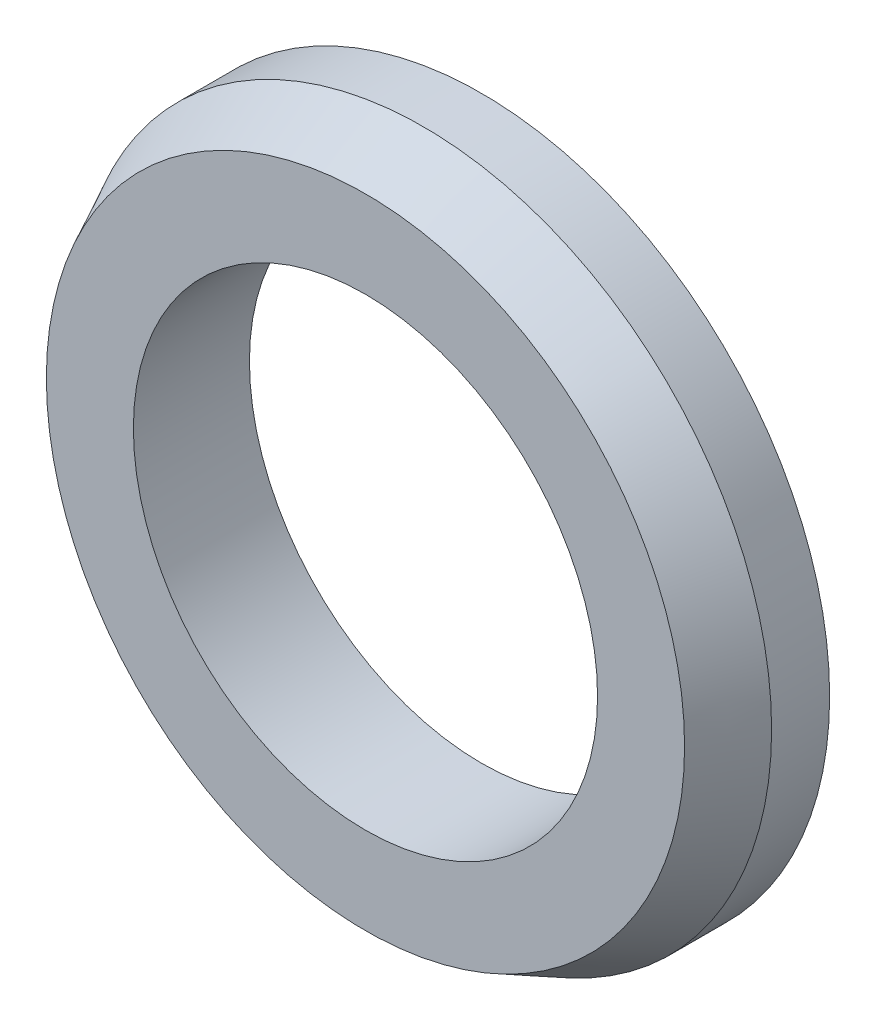
SolidWorks part; units mm, degrees
material "AISI Type 316L stainless steel"
ref_plane "Front Plane" through (0, 0, 0) normal (0, 0, 1) x (1, 0, 0)
ref_plane "Top Plane" through (0, 0, 0) normal (0, 1, 0) x (1, 0, 0)
ref_plane "Right Plane" through (0, 0, 0) normal (1, 0, 0) x (0, 0, -1)
sketch "Sketch1" plane through (0, 0, 0) normal (1, 0, 0) x (0, 0, -1)
  line L0 (0, 0) -> (-34.998, 0) construction
  line L1 (0, 4) -> (0, 6)
  line L2 (0, 6) -> (-1, 6)
  line L3 (-1, 6) -> (-2, 5.5)
  line L4 (-2, 5.5) -> (-2, 4)
  line L5 (-2, 4) -> (0, 4)
  dimension "D1" = 8
  dimension "D2" = 11
  dimension "D3" = 12
  dimension "D4" = 2
  dimension "D5" = 1
revolve "Revolve1" add sketch "Sketch1" angle 360 about L0
